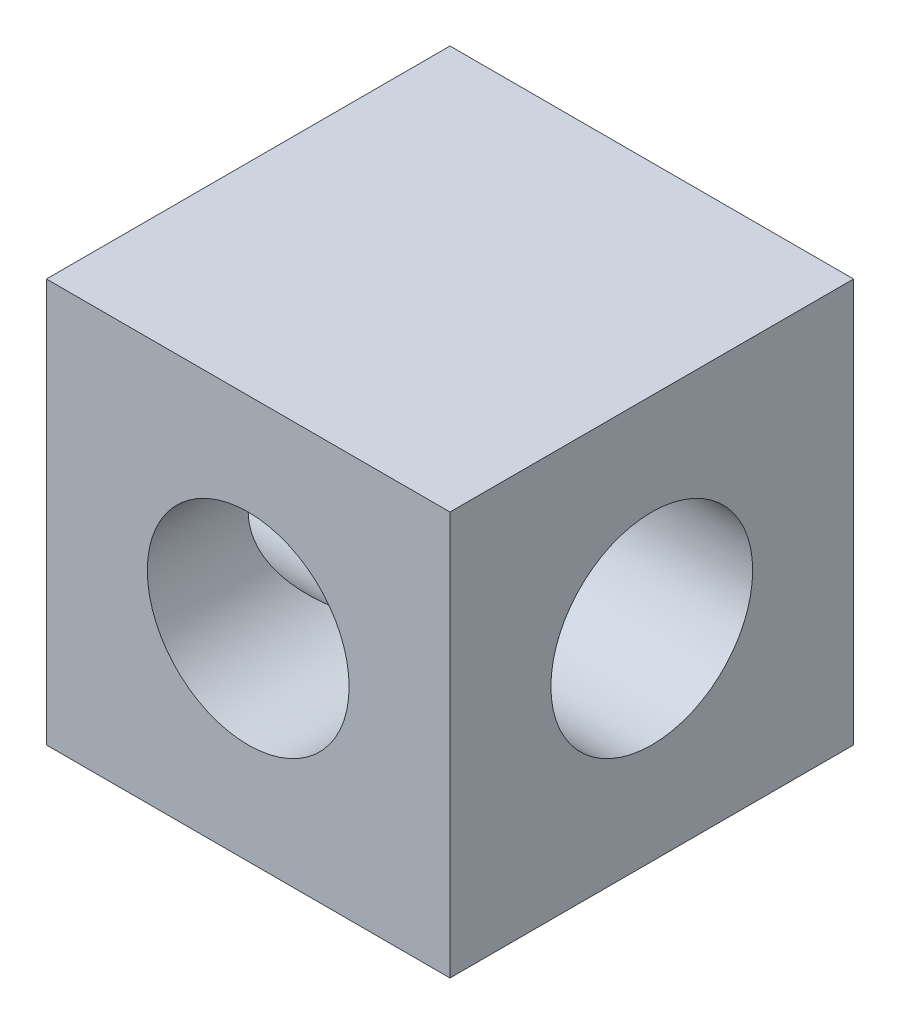
SolidWorks part; units mm, degrees
ref_plane "Front Plane" through (0, 0, 0) normal (0, 0, 1) x (1, 0, 0)
ref_plane "Top Plane" through (0, 0, 0) normal (0, 1, 0) x (1, 0, 0)
ref_plane "Right Plane" through (0, 0, 0) normal (1, 0, 0) x (0, 0, -1)
sketch "Sketch1" plane through (0, 0, 0) normal (0, 1, 0) x (1, 0, 0)
  line L1 (-61.7284, 58.0247) -> (138.2716, 58.0247)
  line L2 (-61.7284, 58.0247) -> (-61.7284, -141.9753)
  line L3 (-61.7284, -141.9753) -> (138.2716, -141.9753)
  line L4 (138.2716, 58.0247) -> (138.2716, -141.9753)
  dimension "D1" = 200
  dimension "D2" = 200
extrude "Boss-Extrude1" add sketch "Sketch1" along normal blind 200
sketch "Sketch2" plane through (-61.7284, 0, 0) normal (-1, 0, 0) x (0, 0, 1)
  line L0 (-58.0247, 200) -> (141.9753, 200) construction
  line L1 (141.9753, 200) -> (141.9753, 0) construction
  circle A0 centre (41.9753, 100) radius 50
  dimension "D3" = 100
  dimension "D1" = 100
  dimension "D2" = 100
extrude "Cut-Extrude2" cut sketch "Sketch2" against normal blind 210
sketch "Sketch4" plane through (0, 0, 141.9753) normal (0, 0, 1) x (1, 0, 0)
  line L0 (-61.7284, 200) -> (138.2716, 200) construction
  line L1 (138.2716, 200) -> (138.2716, 0) construction
  circle A0 centre (38.2716, 100) radius 50
  dimension "D1" = 100
  dimension "D2" = 100
  dimension "D3" = 100
extrude "Cut-Extrude3" cut sketch "Sketch4" against normal blind 100 contours A0
